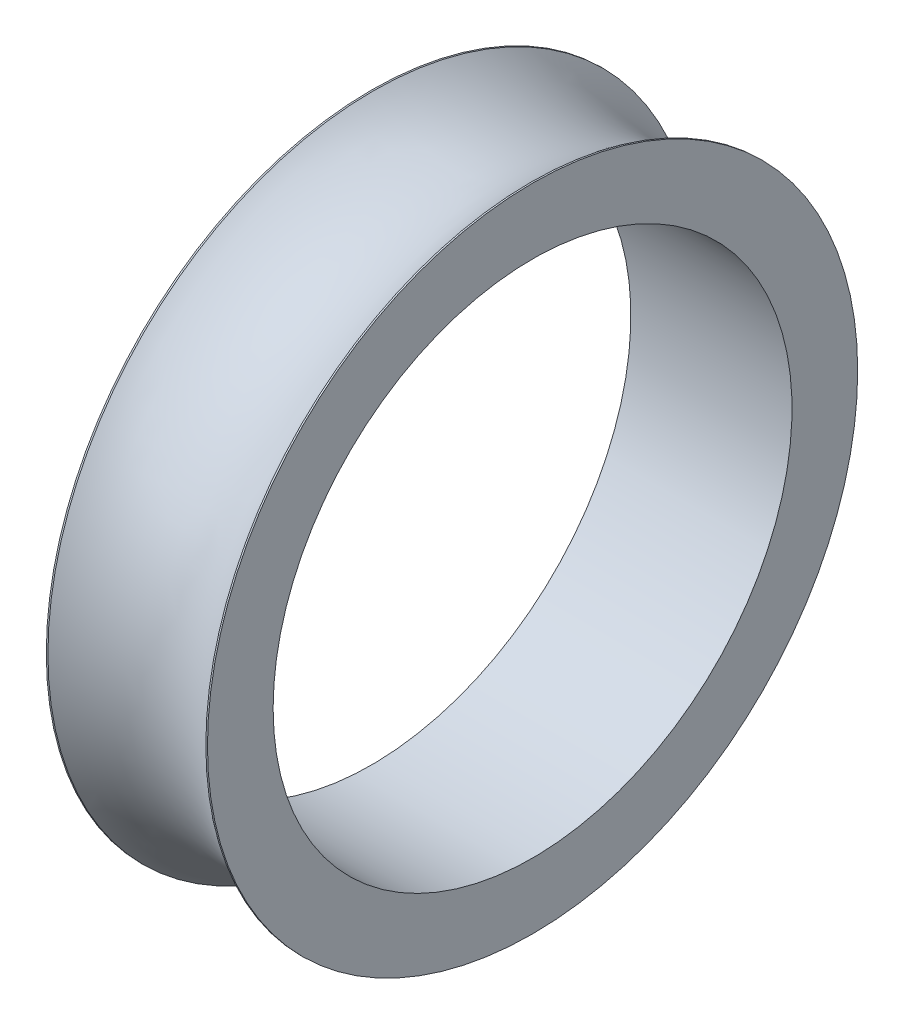
SolidWorks part; units mm, degrees
ref_plane "Front Plane" through (0, 0, 0) normal (0, 0, 1) x (1, 0, 0)
ref_plane "Top Plane" through (0, 0, 0) normal (0, 1, 0) x (1, 0, 0)
ref_plane "Right Plane" through (0, 0, 0) normal (1, 0, 0) x (0, 0, -1)
sketch "Sketch1" plane through (0, 0, 0) normal (0, 0, 1) x (1, 0, 0)
  line L0 (-2.45, -3.1619) -> (-2.5, -3.1619)
  line L1 (-2.5, -13.25) -> (2.5, -13.25) construction
  line L2 (-2.5, -13.25) -> (-2.5, -5.2) construction
  line L3 (-2.5, -5.2) -> (2.5, -5.2)
  line L4 (2.5, -13.25) -> (2.5, -5.2) construction
  line L5 (-2.5, -3.1619) -> (-2.5, -5.2)
  line L6 (2.45, -3.1619) -> (2.5, -3.1619)
  line L7 (2.5, -3.1619) -> (2.5, -5.2)
  circle A0 centre (0, 0) radius 4 construction
  arc A1 (-2.45, -3.1619) -> (2.45, -3.1619) centre (0, 0) ccw
  point P8 (0, -5.2)
  dimension "D3" = 8
  dimension "D5" = 1.2
  dimension "D1" = 5
  dimension "D2" = 8.05
  dimension "D4" = 4.9
revolve "Revolve1" add sketch "Sketch1" angle 360 about L1
